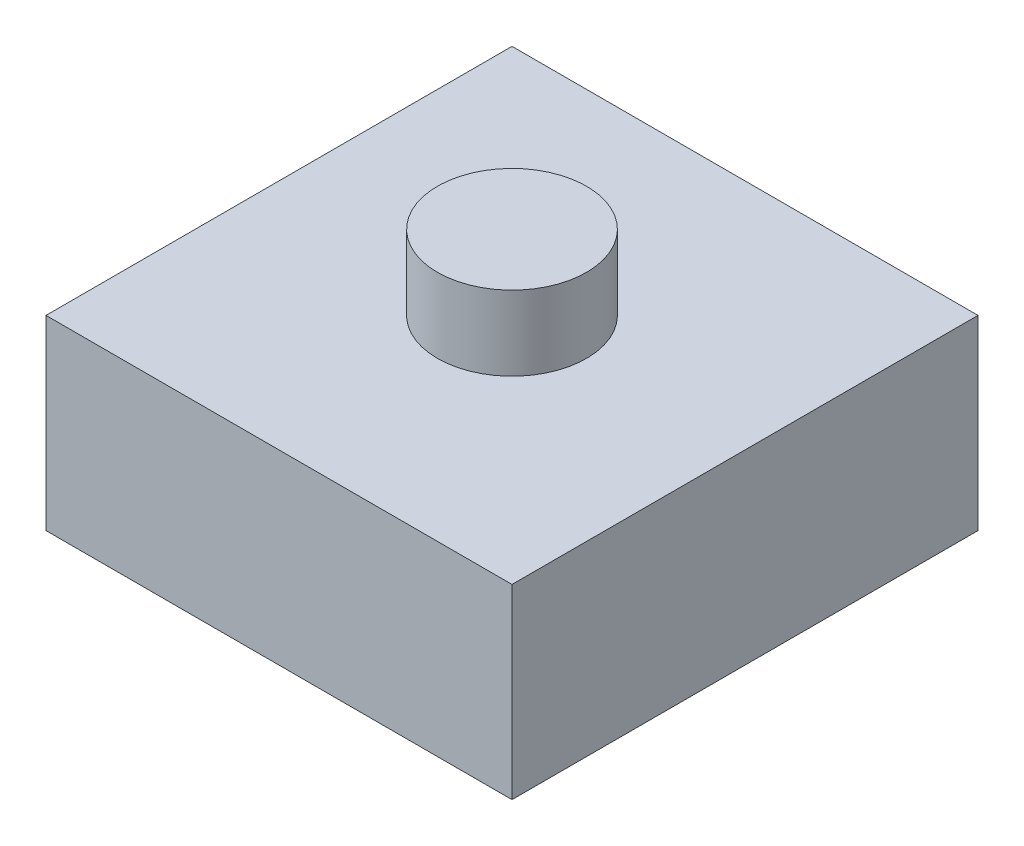
SolidWorks part; units mm, degrees
ref_plane "Front Plane" through (0, 0, 0) normal (0, 0, 1) x (1, 0, 0)
ref_plane "Top Plane" through (0, 0, 0) normal (0, 1, 0) x (1, 0, 0)
ref_plane "Right Plane" through (0, 0, 0) normal (1, 0, 0) x (0, 0, -1)
sketch "Sketch1" plane through (0, 0, 0) normal (0, 1, 0) x (1, 0, 0)
  line L1 (-12.5, -12.5) -> (12.5, -12.5)
  line L2 (-12.5, -12.5) -> (-12.5, 12.5)
  line L3 (-12.5, 12.5) -> (12.5, 12.5)
  line L4 (12.5, -12.5) -> (12.5, 12.5)
  line L5 (-12.5, -12.5) -> (12.5, 12.5) construction
  line L6 (-12.5, 12.5) -> (12.5, -12.5) construction
  point P0 (0, 0)
extrude "Boss-Extrude1" add sketch "Sketch1" along normal blind 10
sketch "Sketch2" plane through (0, 10, 0) normal (0, 1, 0) x (1, 0, 0)
  circle A0 centre (0, 0) radius 4
extrude "Boss-Extrude2" add sketch "Sketch2" along normal blind 4
